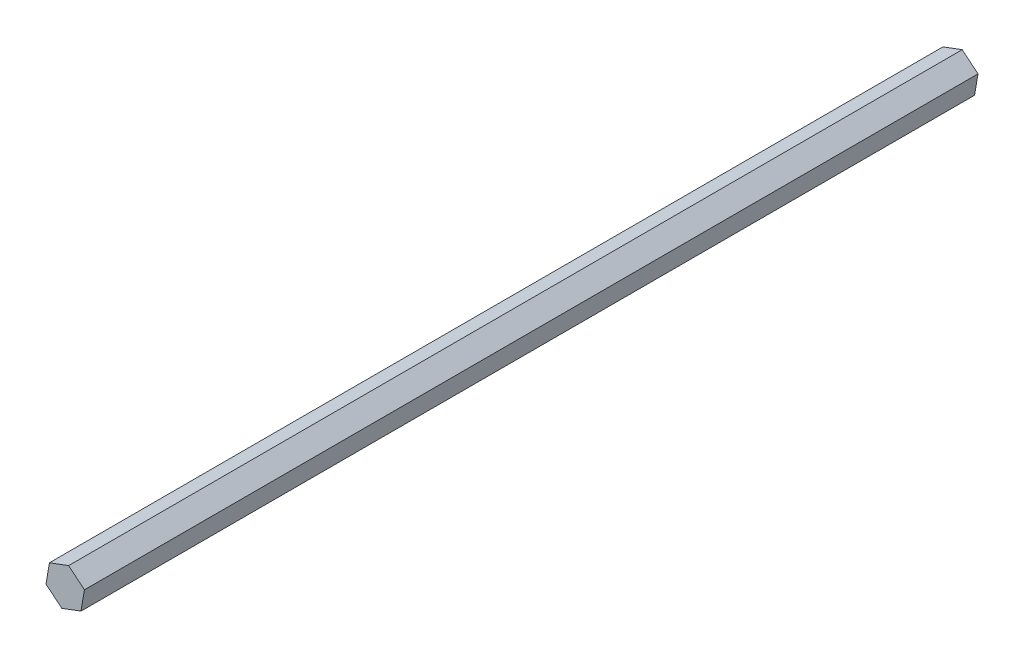
SolidWorks part; units mm, degrees
ref_plane "Front Plane" through (0, 0, 0) normal (0, 0, 1) x (1, 0, 0)
ref_plane "Top Plane" through (0, 0, 0) normal (0, 1, 0) x (1, 0, 0)
ref_plane "Right Plane" through (0, 0, 0) normal (1, 0, 0) x (0, 0, -1)
sketch "Sketch1" plane through (0, 0, 0) normal (0, 0, 1) x (1, 0, 0)
  line L1 (3.1805, -2.6316) -> (3.8693, 1.4386)
  line L2 (3.8693, 1.4386) -> (0.6888, 4.0702)
  line L3 (0.6888, 4.0702) -> (-3.1805, 2.6316)
  line L4 (-3.1805, 2.6316) -> (-3.8693, -1.4386)
  line L5 (-3.8693, -1.4386) -> (-0.6888, -4.0702)
  line L6 (-0.6888, -4.0702) -> (3.1805, -2.6316)
  circle A0 centre (0, 0) radius 3.575 construction
  dimension "D1" = 7.15
extrude "Boss-Extrude1" add sketch "Sketch1" along normal blind 180
